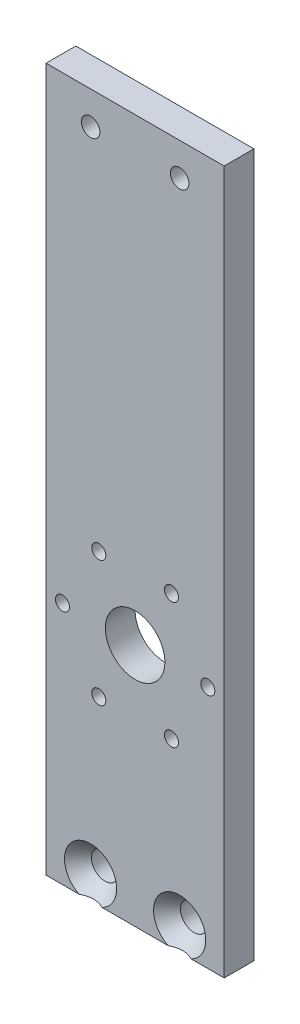
SolidWorks part; units mm, degrees
ref_plane "Alzado" through (0, 0, 0) normal (0, 0, 1) x (1, 0, 0)
ref_plane "Planta" through (0, 0, 0) normal (0, 1, 0) x (1, 0, 0)
ref_plane "Vista lateral" through (0, 0, 0) normal (1, 0, 0) x (0, 0, -1)
sketch "Croquis1" plane through (0, 0, 0) normal (0, 0, 1) x (1, 0, 0)
  line L1 (-19, -75) -> (19, -75)
  line L2 (-19, -75) -> (-19, 75)
  line L3 (-19, 75) -> (19, 75)
  line L4 (19, -75) -> (19, 75)
  line L5 (-19, -75) -> (19, 75) construction
  line L6 (-19, 75) -> (19, -75) construction
  point P0 (0, 0)
  dimension "D1" = 38
  dimension "D2" = 150
extrude "Saliente-Extruir1" add sketch "Croquis1" along normal mid plane 6.35
sketch "Croquis2" plane through (0, 0, -3.175) normal (0, 0, -1) x (-1, 0, 0)
  line L0 (19, 75) -> (19, -75) construction
  line L1 (-19, -75) -> (19, -75)
  line L2 (-19, -75) -> (-19, -68.65)
  line L3 (-19, -68.65) -> (19, -68.65)
  line L4 (19, -75) -> (19, -68.65)
  dimension "D1" = 6.35
sketch "Croquis3" plane through (0, 0, 3.175) normal (0, 0, 1) x (1, 0, 0)
  line L0 (0, 99.9235) -> (0, -102.4325) construction
  line L1 (-92.4199, 0) -> (74.7437, 0) construction
  line L2 (-19, -75) -> (19, -75) construction
  line L3 (27.734, -23) -> (-27.5116, -23) construction
  circle A0 centre (0, -23) radius 6.35
  circle A1 centre (-15.5, -23) radius 1.5
  circle A2 centre (0, -23) radius 15.5 construction
  circle A3 centre (-7.75, -9.5766) radius 1.5
  circle A4 centre (7.75, -9.5766) radius 1.5
  circle A5 centre (15.5, -23) radius 1.5
  circle A6 centre (7.75, -36.4234) radius 1.5
  circle A7 centre (-7.75, -36.4234) radius 1.5
  point P27 (0, -23)
  dimension "D1" = 12.7
  dimension "D3" = 3
  dimension "D5" = 31
  dimension "D2" = 52
  dimension "D4" = 15.5
  dimension "D7" = 7.75
  dimension "D6" = 6
extrude "Cortar-Extruir2" cut sketch "Croquis3" against normal blind 25.4
sketch "Croquis5" plane through (0, 0, 3.175) normal (0, 0, 1) x (1, 0, 0)
  line L0 (-36.7484, -62) -> (34.3572, -62) construction
  line L1 (-19, -75) -> (19, -75) construction
  line L2 (0, 90.5631) -> (0, -113.4154) construction
  circle A0 centre (-9.5, -70) radius 1.9844
  circle A1 centre (9.5, -70) radius 1.9844
  dimension "D2" = 3.9688
  dimension "D1" = 13
  dimension "D3" = 9.5
  dimension "D4" = 8
hole_wizard "Avellanado para tornillo con cabeza ovalada de #121" positions "Croquis3D1" profile "Croquis6" countersink size "#12" standard "Ansi Inch"
sketch3d "Croquis3D1"
  point P0 (-9.5, -70, 3.175)
  point P3 (9.5, -70, 3.175)
sketch "Croquis6" plane through (-9.5, -70, 3.175) normal (1, 0, 0) x (0, -1, 0)
  line L0 (0, 0) -> (0, 21.7399)
  line L1 (0, 21.7399) -> (2.8956, 20)
  line L2 (2.8956, 20) -> (2.8956, 3.068)
  line L3 (2.8956, 3.068) -> (5.5626, 0)
  line L5 (5.5626, 0) -> (0, 0)
  line L6 (-2.8956, 3.068) -> (-5.5626, 0) construction
  line L10 (0, 21.7399) -> (-2.8956, 20) construction
  line L11 (0, -6.35) -> (0, 107.95) construction
  dimension "Diámetro de taladro" = 5.7912
  dimension "Profundidad de taladro" = 20
  dimension "Ángulo de avellanado cercano" = 11.1252
  dimension "Ángulo de avellanado lejano" = 82
  dimension "Ángulo de perforador" = 118
sketch "Croquis7" plane through (0, 0, 3.175) normal (0, 0, 1) x (1, 0, 0)
  line L0 (-22.8478, 62) -> (24.0607, 62) construction
  line L1 (19, 75) -> (-19, 75) construction
  line L3 (0, 90.5631) -> (0, -113.4154) construction
  line L4 (0, 114.7105) -> (0, -90.3524) construction
  circle A0 centre (-9.5, 68) radius 1.9844
  circle A1 centre (9.5, 68) radius 1.9844
  dimension "D4" = 3.9688
  dimension "D1" = 13
  dimension "D2" = 6
  dimension "D3" = 9.5
extrude "Cortar-Extruir3" cut sketch "Croquis7" against normal blind 25.4 contours A1 | A0
